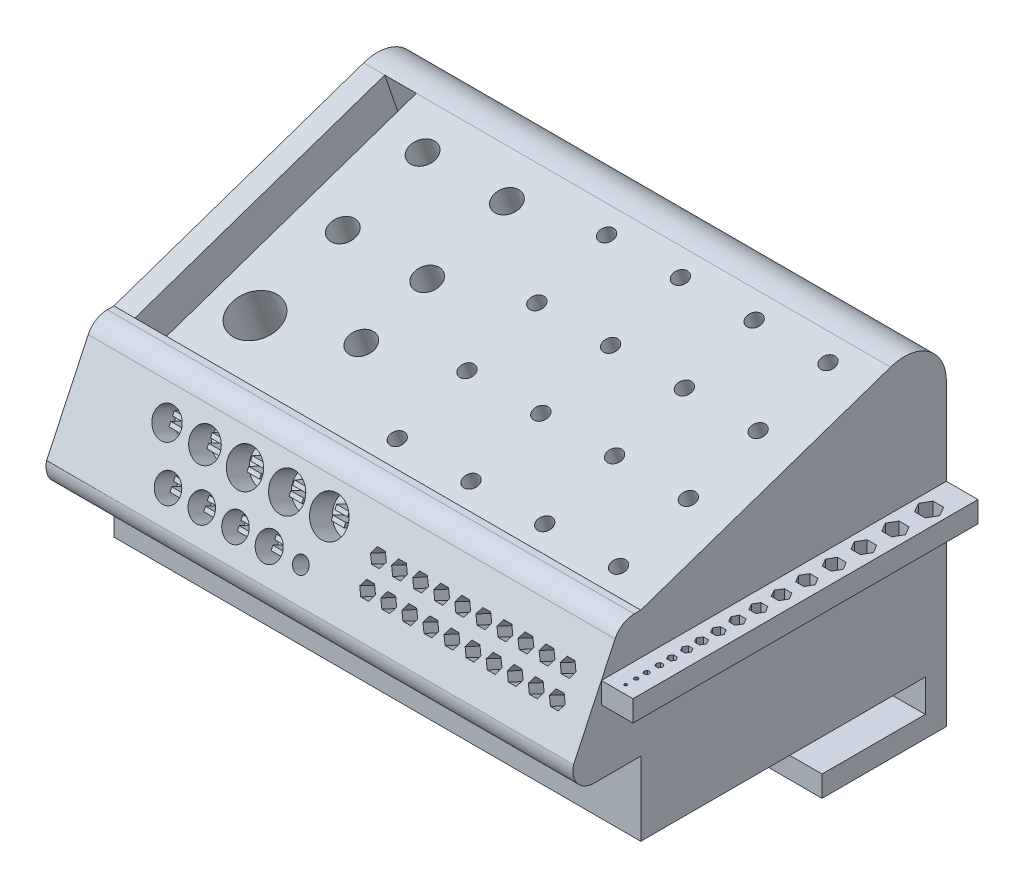
SolidWorks part; units mm, degrees
ref_plane "Front Plane" through (0, 0, 0) normal (0, 0, 1) x (1, 0, 0)
ref_plane "Top Plane" through (0, 0, 0) normal (0, 1, 0) x (1, 0, 0)
ref_plane "Right Plane" through (0, 0, 0) normal (1, 0, 0) x (0, 0, -1)
sketch "Sketch1" plane through (0, 0, 0) normal (1, 0, 0) x (0, 0, -1)
  line L0 (0, 0) -> (-49, 0)
  line L1 (0, 0) -> (0, 15.35)
  line L2 (-49, 0) -> (-49, -10)
  line L3 (-49, -10) -> (10, -10)
  line L4 (0, 15.35) -> (-135, 15.35)
  line L7 (-135, 15.35) -> (-135, 110.35)
  line L8 (10, -10) -> (10, 132.0117)
  line L9 (-135, 110.35) -> (-16.479, 150.9332)
  arc A0 (10, 132.0117) -> (-16.479, 150.9332) centre (-10, 132.0117) ccw
  point P11 (10, 160)
  dimension "D7" = 20
  dimension "D1" = 49
  dimension "D2" = 15.35
  dimension "D3" = 10
  dimension "D4" = 59
  dimension "D5" = 135
  dimension "D6" = 170
  dimension "D8" = 95
extrude "Boss-Extrude1" add sketch "Sketch1" along normal blind 250
sketch "Sketch2" plane through (0, 140.1443, 47.9874) normal (0, 0.9461, 0.3239) x (1, 0, 0)
  line L2 (250, -81.9723) -> (0, -81.9723) construction
  line L3 (250, 33.3043) -> (250, -91.9723) construction
  line L4 (0, 33.3043) -> (0, -91.9723) construction
  line L5 (0, -46.9723) -> (250, -46.9723) construction
  line L6 (0, -11.9723) -> (250, -11.9723) construction
  line L7 (250, 23.0277) -> (0, 23.0277) construction
  line L8 (230, -91.9723) -> (230, 33.3043) construction
  line L9 (250, -91.9723) -> (0, -91.9723) construction
  line L10 (250, 33.3043) -> (0, 33.3043) construction
  line L11 (195, -91.9723) -> (195, 33.3043) construction
  line L12 (160, -91.9723) -> (160, 33.3043) construction
  line L13 (125, -91.9723) -> (125, 33.3043) construction
  circle A0 centre (230, -81.9723) radius 3.5
  circle A1 centre (230, -46.9723) radius 3.5
  circle A2 centre (230, -11.9723) radius 3.5
  circle A3 centre (230, 23.0277) radius 3.5
  circle A5 centre (195, -81.9723) radius 3.5
  circle A6 centre (195, -46.9723) radius 3.5
  circle A7 centre (195, -11.9723) radius 3.5
  circle A8 centre (195, 23.0277) radius 3.5
  circle A9 centre (160, -81.9723) radius 3.5
  circle A10 centre (160, -46.9723) radius 3.5
  circle A11 centre (160, -11.9723) radius 3.5
  circle A12 centre (160, 23.0277) radius 3.5
  circle A13 centre (125, -81.9723) radius 3.5
  circle A14 centre (125, -46.9723) radius 3.5
  circle A15 centre (125, -11.9723) radius 3.5
  circle A16 centre (125, 23.0277) radius 3.5
  point P42 (230, -71.6708)
  point P45 (230, -1.6708)
  point P48 (230, 33.3292)
  point P49 (195, 33.3292)
  point P52 (195, -1.6708)
  point P55 (195, -36.6708)
  point P58 (195, -71.6708)
  point P61 (160, -71.6708)
  point P64 (125, -71.6708)
  point P65 (125, -36.6708)
  point P66 (125, -1.6708)
  point P67 (125, 33.3292)
  point P68 (125, 33.3292)
  point P69 (160, 33.3292)
  point P70 (160, -1.6708)
  point P71 (160, -36.6708)
  dimension "D1" = 10
  dimension "D2" = 35
  dimension "D3" = 35
  dimension "D4" = 35
  dimension "D5" = 20
  dimension "D6" = 35
  dimension "D7" = 35
  dimension "D8" = 35
extrude "Cut-Extrude1" cut sketch "Sketch2" against normal blind 80
sketch "Sketch3" plane through (0, 140.1443, 47.9874) normal (0, 0.9461, 0.3239) x (1, 0, 0)
  line L0 (105, 33.3043) -> (105, -91.9723) construction
  line L1 (250, 33.3043) -> (0, 33.3043) construction
  line L2 (250, -91.9723) -> (0, -91.9723) construction
  line L3 (105, 15.3043) -> (0, 15.3043) construction
  line L4 (0, 33.3043) -> (0, -91.9723) construction
  line L5 (85, 33.3043) -> (85, -91.9723) construction
  line L6 (105, -24.6957) -> (0, -24.6957) construction
  line L7 (105, -64.6957) -> (0, -64.6957) construction
  line L8 (45, 33.3043) -> (45, -91.9723) construction
  line L9 (25, 33.3043) -> (25, -91.9723) construction
  line L11 (25, 33.3043) -> (10, 33.3043)
  line L12 (25, 33.3043) -> (25, -91.9723)
  line L13 (25, -91.9723) -> (10, -91.9723)
  line L14 (10, 33.3043) -> (10, -91.9723)
  circle A0 centre (125, -46.9723) radius 3.5 construction
  circle A1 centre (85, 15.3043) radius 6
  circle A2 centre (85, -24.6957) radius 6
  circle A3 centre (85, -57.7346) radius 6
  circle A4 centre (45, 15.3043) radius 6
  circle A5 centre (45, -24.6957) radius 6
  circle A7 centre (45, -68.746) radius 11
  dimension "D2" = 12
  dimension "D11" = 22
  dimension "D1" = 20
  dimension "D3" = 18
  dimension "D4" = 20
  dimension "D5" = 40
  dimension "D6" = 40
  dimension "D7" = 40
  dimension "D8" = 20
  dimension "D9" = 15
  dimension "D10" = 0
extrude "Cut-Extrude3" cut sketch "Sketch3" against normal blind 80
sketch "Sketch5" plane through (0, 0, 135) normal (0, 0, 1) x (1, 0, 0)
  line L0 (250, 110.35) -> (250, 15.35) construction
  line L1 (250, 110.35) -> (0, 110.35)
  line L2 (250, 110.35) -> (250, 50.35)
  line L3 (250, 50.35) -> (0, 50.35)
  line L4 (0, 110.35) -> (0, 50.35)
  line L5 (0, 110.35) -> (0, 15.35) construction
  line L7 (250, 15.35) -> (0, 15.35) construction
  line L8 (250, 110.35) -> (25, 110.35) construction
  dimension "D1" = 35
  dimension "D2" = 0
extrude "Boss-Extrude3" add sketch "Sketch5" along normal blind 35
sketch "Sketch6" plane through (250, 0, 0) normal (1, 0, 0) x (0, 0, -1)
  line L0 (-135, 15.35) -> (-135, 110.35) construction
  line L1 (-135, 110.35) -> (-147.1922, 110.35) construction
  line L2 (-170, 110.35) -> (-135, 110.35) construction
  line L4 (-135, 50.35) -> (-157.1922, 50.35) construction
  line L5 (-157.1922, 50.35) -> (-170, 50.35)
  line L7 (-170, 110.35) -> (-170, 50.35)
  line L8 (-138.1305, 110.35) -> (-135, 110.35)
  line L9 (-166.8937, 62.7754) -> (-147.1763, 104.6131)
  arc A0 (-157.1922, 50.35) -> (-166.8937, 62.7754) centre (-157.1922, 60.35) cw
  arc A2 (-138.1305, 110.35) -> (-147.1763, 104.6131) centre (-138.1305, 100.35) ccw
  point P13 (-170, 50.35)
  point P15 (-170, 50.35)
  point P18 (-155, 110.35)
  dimension "D2" = 10
  dimension "D3" = 10
  dimension "D1" = 20
extrude "Cut-Extrude4" cut sketch "Sketch6" against normal through all
sketch "Sketch8" plane through (0, 75.7683, 160.7703) normal (0, 0.4263, 0.9046) x (1, 0, 0)
  line L0 (130, 29.3807) -> (130, -11.8503) construction
  line L1 (130, 8.7652) -> (250, 8.7652) construction
  line L2 (130, 2.7652) -> (250, 2.7652) construction
  line L3 (130, 14.7652) -> (250, 14.7652) construction
  line L4 (145, 14.7652) -> (145, 2.7652) construction
  line L5 (155, 14.7652) -> (155, 2.7652) construction
  line L6 (165, 14.7652) -> (165, 2.7652) construction
  line L7 (175, 14.7652) -> (175, 2.7652) construction
  line L8 (185, 14.7652) -> (185, 2.7652) construction
  line L9 (195, 14.7652) -> (195, 2.7652) construction
  line L10 (205, 14.7652) -> (205, 2.7652) construction
  line L11 (215, 14.7652) -> (215, 2.7652) construction
  line L12 (225, 14.7652) -> (225, 2.7652) construction
  line L13 (235, 14.7652) -> (235, 2.7652) construction
  line L14 (141.2472, 14.7652) -> (143.1236, 11.5152)
  line L15 (143.1236, 11.5152) -> (146.8764, 11.5152)
  line L16 (146.8764, 11.5152) -> (148.7528, 14.7652)
  line L17 (148.7528, 14.7652) -> (146.8764, 18.0152)
  line L18 (146.8764, 18.0152) -> (143.1236, 18.0152)
  line L19 (143.1236, 18.0152) -> (141.2472, 14.7652)
  line L20 (151.2472, 14.7652) -> (153.1236, 11.5152)
  line L21 (153.1236, 11.5152) -> (156.8764, 11.5152)
  line L22 (156.8764, 11.5152) -> (158.7528, 14.7652)
  line L23 (158.7528, 14.7652) -> (156.8764, 18.0152)
  line L24 (156.8764, 18.0152) -> (153.1236, 18.0152)
  line L25 (153.1236, 18.0152) -> (151.2472, 14.7652)
  line L26 (161.2472, 14.7652) -> (163.1236, 11.5152)
  line L27 (163.1236, 11.5152) -> (166.8764, 11.5152)
  line L28 (166.8764, 11.5152) -> (168.7528, 14.7652)
  line L29 (168.7528, 14.7652) -> (166.8764, 18.0152)
  line L30 (166.8764, 18.0152) -> (163.1236, 18.0152)
  line L31 (163.1236, 18.0152) -> (161.2472, 14.7652)
  line L32 (171.2472, 14.7652) -> (173.1236, 11.5152)
  line L33 (173.1236, 11.5152) -> (176.8764, 11.5152)
  line L34 (176.8764, 11.5152) -> (178.7528, 14.7652)
  line L35 (178.7528, 14.7652) -> (176.8764, 18.0152)
  line L36 (176.8764, 18.0152) -> (173.1236, 18.0152)
  line L37 (173.1236, 18.0152) -> (171.2472, 14.7652)
  line L38 (181.2472, 14.7652) -> (183.1236, 11.5152)
  line L39 (183.1236, 11.5152) -> (186.8764, 11.5152)
  line L40 (186.8764, 11.5152) -> (188.7528, 14.7652)
  line L41 (188.7528, 14.7652) -> (186.8764, 18.0152)
  line L42 (186.8764, 18.0152) -> (183.1236, 18.0152)
  line L43 (183.1236, 18.0152) -> (181.2472, 14.7652)
  line L44 (191.2472, 14.7652) -> (193.1236, 11.5152)
  line L45 (193.1236, 11.5152) -> (196.8764, 11.5152)
  line L46 (196.8764, 11.5152) -> (198.7528, 14.7652)
  line L47 (198.7528, 14.7652) -> (196.8764, 18.0152)
  line L48 (196.8764, 18.0152) -> (193.1236, 18.0152)
  line L49 (193.1236, 18.0152) -> (191.2472, 14.7652)
  line L50 (201.2472, 14.7652) -> (203.1236, 11.5152)
  line L51 (203.1236, 11.5152) -> (206.8764, 11.5152)
  line L52 (206.8764, 11.5152) -> (208.7528, 14.7652)
  line L53 (208.7528, 14.7652) -> (206.8764, 18.0152)
  line L54 (206.8764, 18.0152) -> (203.1236, 18.0152)
  line L55 (203.1236, 18.0152) -> (201.2472, 14.7652)
  line L56 (211.2472, 14.7652) -> (213.1236, 11.5152)
  line L57 (213.1236, 11.5152) -> (216.8764, 11.5152)
  line L58 (216.8764, 11.5152) -> (218.7528, 14.7652)
  line L59 (218.7528, 14.7652) -> (216.8764, 18.0152)
  line L60 (216.8764, 18.0152) -> (213.1236, 18.0152)
  line L61 (213.1236, 18.0152) -> (211.2472, 14.7652)
  line L62 (221.2472, 14.7652) -> (223.1236, 11.5152)
  line L63 (223.1236, 11.5152) -> (226.8764, 11.5152)
  line L64 (226.8764, 11.5152) -> (228.7528, 14.7652)
  line L65 (228.7528, 14.7652) -> (226.8764, 18.0152)
  line L66 (226.8764, 18.0152) -> (223.1236, 18.0152)
  line L67 (223.1236, 18.0152) -> (221.2472, 14.7652)
  line L68 (231.2472, 14.7652) -> (233.1236, 11.5152)
  line L69 (233.1236, 11.5152) -> (236.8764, 11.5152)
  line L70 (236.8764, 11.5152) -> (238.7528, 14.7652)
  line L71 (238.7528, 14.7652) -> (236.8764, 18.0152)
  line L72 (236.8764, 18.0152) -> (233.1236, 18.0152)
  line L73 (233.1236, 18.0152) -> (231.2472, 14.7652)
  line L74 (231.2472, 2.7652) -> (233.1236, -0.4848)
  line L75 (233.1236, -0.4848) -> (236.8764, -0.4848)
  line L76 (236.8764, -0.4848) -> (238.7528, 2.7652)
  line L77 (238.7528, 2.7652) -> (236.8764, 6.0152)
  line L78 (236.8764, 6.0152) -> (233.1236, 6.0152)
  line L79 (233.1236, 6.0152) -> (231.2472, 2.7652)
  line L80 (221.2472, 2.7652) -> (223.1236, -0.4848)
  line L81 (223.1236, -0.4848) -> (226.8764, -0.4848)
  line L82 (226.8764, -0.4848) -> (228.7528, 2.7652)
  line L83 (228.7528, 2.7652) -> (226.8764, 6.0152)
  line L84 (226.8764, 6.0152) -> (223.1236, 6.0152)
  line L85 (223.1236, 6.0152) -> (221.2472, 2.7652)
  line L86 (211.2472, 2.7652) -> (213.1236, -0.4848)
  line L87 (213.1236, -0.4848) -> (216.8764, -0.4848)
  line L88 (216.8764, -0.4848) -> (218.7528, 2.7652)
  line L89 (218.7528, 2.7652) -> (216.8764, 6.0152)
  line L90 (216.8764, 6.0152) -> (213.1236, 6.0152)
  line L91 (213.1236, 6.0152) -> (211.2472, 2.7652)
  line L92 (201.2472, 2.7652) -> (203.1236, -0.4848)
  line L93 (203.1236, -0.4848) -> (206.8764, -0.4848)
  line L94 (206.8764, -0.4848) -> (208.7528, 2.7652)
  line L95 (208.7528, 2.7652) -> (206.8764, 6.0152)
  line L96 (206.8764, 6.0152) -> (203.1236, 6.0152)
  line L97 (203.1236, 6.0152) -> (201.2472, 2.7652)
  line L98 (191.2472, 2.7652) -> (193.1236, -0.4848)
  line L99 (193.1236, -0.4848) -> (196.8764, -0.4848)
  line L100 (196.8764, -0.4848) -> (198.7528, 2.7652)
  line L101 (198.7528, 2.7652) -> (196.8764, 6.0152)
  line L102 (196.8764, 6.0152) -> (193.1236, 6.0152)
  line L103 (193.1236, 6.0152) -> (191.2472, 2.7652)
  line L104 (181.2472, 2.7652) -> (183.1236, -0.4848)
  line L105 (183.1236, -0.4848) -> (186.8764, -0.4848)
  line L106 (186.8764, -0.4848) -> (188.7528, 2.7652)
  line L107 (188.7528, 2.7652) -> (186.8764, 6.0152)
  line L108 (186.8764, 6.0152) -> (183.1236, 6.0152)
  line L109 (183.1236, 6.0152) -> (181.2472, 2.7652)
  line L110 (171.2472, 2.7652) -> (173.1236, -0.4848)
  line L111 (173.1236, -0.4848) -> (176.8764, -0.4848)
  line L112 (176.8764, -0.4848) -> (178.7528, 2.7652)
  line L113 (178.7528, 2.7652) -> (176.8764, 6.0152)
  line L114 (176.8764, 6.0152) -> (173.1236, 6.0152)
  line L115 (173.1236, 6.0152) -> (171.2472, 2.7652)
  line L116 (161.2472, 2.7652) -> (163.1236, -0.4848)
  line L117 (163.1236, -0.4848) -> (166.8764, -0.4848)
  line L118 (166.8764, -0.4848) -> (168.7528, 2.7652)
  line L119 (168.7528, 2.7652) -> (166.8764, 6.0152)
  line L120 (166.8764, 6.0152) -> (163.1236, 6.0152)
  line L121 (163.1236, 6.0152) -> (161.2472, 2.7652)
  line L122 (151.2472, 2.7652) -> (153.1236, -0.4848)
  line L123 (153.1236, -0.4848) -> (156.8764, -0.4848)
  line L124 (156.8764, -0.4848) -> (158.7528, 2.7652)
  line L125 (158.7528, 2.7652) -> (156.8764, 6.0152)
  line L126 (156.8764, 6.0152) -> (153.1236, 6.0152)
  line L127 (153.1236, 6.0152) -> (151.2472, 2.7652)
  line L128 (141.2472, 2.7652) -> (143.1236, -0.4848)
  line L129 (143.1236, -0.4848) -> (146.8764, -0.4848)
  line L130 (146.8764, -0.4848) -> (148.7528, 2.7652)
  line L131 (148.7528, 2.7652) -> (146.8764, 6.0152)
  line L132 (146.8764, 6.0152) -> (143.1236, 6.0152)
  line L133 (143.1236, 6.0152) -> (141.2472, 2.7652)
  line L134 (250, -14.3635) -> (250, 31.8877) construction
  line L135 (250, 31.8877) -> (0, 31.8877) construction
  circle A0 centre (145, 14.7652) radius 3.25 construction
  circle A1 centre (155, 14.7652) radius 3.25 construction
  circle A2 centre (165, 14.7652) radius 3.25 construction
  circle A3 centre (175, 14.7652) radius 3.25 construction
  circle A4 centre (185, 14.7652) radius 3.25 construction
  circle A5 centre (195, 14.7652) radius 3.25 construction
  circle A6 centre (205, 14.7652) radius 3.25 construction
  circle A7 centre (215, 14.7652) radius 3.25 construction
  circle A8 centre (225, 14.7652) radius 3.25 construction
  circle A9 centre (235, 14.7652) radius 3.25 construction
  circle A10 centre (235, 2.7652) radius 3.25 construction
  circle A11 centre (225, 2.7652) radius 3.25 construction
  circle A12 centre (215, 2.7652) radius 3.25 construction
  circle A13 centre (205, 2.7652) radius 3.25 construction
  circle A14 centre (195, 2.7652) radius 3.25 construction
  circle A15 centre (185, 2.7652) radius 3.25 construction
  circle A16 centre (175, 2.7652) radius 3.25 construction
  circle A17 centre (165, 2.7652) radius 3.25 construction
  circle A18 centre (155, 2.7652) radius 3.25 construction
  circle A19 centre (145, 2.7652) radius 3.25 construction
  dimension "D12" = 6.5
  dimension "D13" = 6.5
  dimension "D14" = 6.5
  dimension "D15" = 6.5
  dimension "D16" = 6.5
  dimension "D17" = 6.5
  dimension "D18" = 6.5
  dimension "D19" = 6.5
  dimension "D20" = 6.5
  dimension "D21" = 6.5
  dimension "D22" = 6.5
  dimension "D23" = 6.5
  dimension "D24" = 6.5
  dimension "D25" = 6.5
  dimension "D26" = 6.5
  dimension "D27" = 6.5
  dimension "D28" = 6.5
  dimension "D29" = 6.5
  dimension "D30" = 6.5
  dimension "D31" = 6.5
  dimension "D1" = 6
  dimension "D2" = 6
  dimension "D3" = 10
  dimension "D4" = 10
  dimension "D5" = 10
  dimension "D6" = 10
  dimension "D7" = 10
  dimension "D8" = 10
  dimension "D9" = 10
  dimension "D10" = 10
  dimension "D11" = 10
  dimension "D32" = 15
  dimension "D33" = 23.1225
extrude "Cut-Extrude6" cut sketch "Sketch8" against normal blind 15
sketch "Sketch9" plane through (0, 75.7683, 160.7703) normal (0, 0.4263, 0.9046) x (1, 0, 0)
  line L0 (130, 31.8877) -> (130, -14.3635) construction
  line L1 (250, 31.8877) -> (0, 31.8877) construction
  line L2 (250, -14.3635) -> (0, -14.3635) construction
  line L3 (250, -14.3635) -> (250, 31.8877) construction
  line L4 (130, 8.7621) -> (0, 8.7621) construction
  line L5 (0, 31.8877) -> (0, -14.3635) construction
  line L6 (130, 18.7621) -> (0, 18.7621) construction
  line L7 (130, -1.2379) -> (0, -1.2379) construction
  circle A0 centre (120, 18.7621) radius 8.625
  circle A1 centre (100, 18.7621) radius 8.125
  circle A2 centre (80, 18.7621) radius 8.125
  circle A3 centre (61, 18.7621) radius 7.125
  circle A4 centre (43, 18.7621) radius 6.625
  circle A5 centre (100, -1.2379) radius 6.125
  circle A6 centre (115, -1.2379) radius 3.625
  circle A7 centre (84, -1.2379) radius 6
  circle A8 centre (68, -1.2379) radius 6
  circle A9 centre (52, -1.2379) radius 6
  dimension "D4" = 17.25
  dimension "D6" = 16.25
  dimension "D8" = 16.25
  dimension "D10" = 14.25
  dimension "D12" = 13.25
  dimension "D14" = 12.25
  dimension "D15" = 7.25
  dimension "D18" = 12
  dimension "D20" = 12
  dimension "D22" = 12
  dimension "D1" = 120
  dimension "D2" = 10
  dimension "D3" = 10
  dimension "D5" = 10
  dimension "D7" = 20
  dimension "D9" = 20
  dimension "D11" = 19
  dimension "D13" = 18
  dimension "D16" = 15
  dimension "D17" = 15
  dimension "D19" = 16
  dimension "D21" = 16
  dimension "D23" = 16
extrude "Cut-Extrude7" cut sketch "Sketch9" against normal blind 12
sketch "Sketch10" plane through (0, 70.6525, 149.9154) normal (0, 0.4263, 0.9046) x (1, 0, 0)
  line L0 (120, 27.3871) -> (120, 10.1371) construction
  line L1 (128.625, 18.7621) -> (111.375, 18.7621) construction
  line L2 (111.375, 18.7621) -> (108.125, 18.7621) construction
  line L3 (108.125, 18.7621) -> (91.875, 18.7621) construction
  line L4 (91.875, 18.7621) -> (88.125, 18.7621) construction
  line L5 (88.125, 18.7621) -> (71.875, 18.7621) construction
  line L6 (71.875, 18.7621) -> (68.125, 18.7621) construction
  line L7 (68.125, 18.7621) -> (53.875, 18.7621) construction
  line L8 (53.875, 18.7621) -> (49.625, 18.7621) construction
  line L9 (49.625, 18.7621) -> (36.375, 18.7621) construction
  line L10 (46, -1.2379) -> (58, -1.2379) construction
  line L11 (58, -1.2379) -> (62, -1.2379) construction
  line L12 (62, -1.2379) -> (74, -1.2379) construction
  line L13 (74, -1.2379) -> (78, -1.2379) construction
  line L14 (78, -1.2379) -> (90, -1.2379) construction
  line L15 (90, -1.2379) -> (93.875, -1.2379) construction
  line L16 (93.875, -1.2379) -> (106.125, -1.2379) construction
  line L17 (106.125, -1.2379) -> (111.375, -1.2379) construction
  line L18 (111.375, -1.2379) -> (118.625, -1.2379) construction
  line L19 (100, 26.8871) -> (100, 10.6371) construction
  line L20 (80, 26.8871) -> (80, 10.6371) construction
  line L21 (61, 25.8871) -> (61, 11.6371) construction
  line L22 (43, 25.3871) -> (43, 12.1371) construction
  line L23 (52, 4.7621) -> (52, -7.2379) construction
  line L24 (68, 4.7621) -> (68, -7.2379) construction
  line L25 (84, 4.7621) -> (84, -7.2379) construction
  line L26 (100, 4.8871) -> (100, -7.3629) construction
  line L27 (115, 2.3871) -> (115, -4.8629) construction
  line L28 (97, 21.7621) -> (103, 21.7621)
  line L33 (117, 21.7621) -> (123, 21.7621)
  line L34 (117, 21.7621) -> (117, 19.7621)
  line L39 (117, 19.7621) -> (123, 19.7621)
  line L40 (123, 21.7621) -> (123, 19.7621)
  line L41 (117, 17.7621) -> (123, 17.7621)
  line L42 (117, 17.7621) -> (117, 15.7621)
  line L43 (117, 15.7621) -> (123, 15.7621)
  line L44 (123, 17.7621) -> (123, 15.7621)
  line L45 (97, 21.7621) -> (97, 19.7621)
  line L46 (97, 19.7621) -> (103, 19.7621)
  line L47 (103, 21.7621) -> (103, 19.7621)
  line L48 (97, 17.7621) -> (103, 17.7621)
  line L49 (97, 17.7621) -> (97, 15.7621)
  line L50 (97, 15.7621) -> (103, 15.7621)
  line L51 (103, 17.7621) -> (103, 15.7621)
  line L52 (77, 21.7621) -> (83, 21.7621)
  line L53 (77, 21.7621) -> (77, 19.7621)
  line L54 (77, 19.7621) -> (83, 19.7621)
  line L55 (83, 21.7621) -> (83, 19.7621)
  line L56 (77, 17.7621) -> (83, 17.7621)
  line L57 (77, 17.7621) -> (77, 15.7621)
  line L58 (77, 15.7621) -> (83, 15.7621)
  line L59 (83, 17.7621) -> (83, 15.7621)
  line L60 (58.0009, 21.7621) -> (64.0009, 21.7621)
  line L61 (58.0009, 21.7621) -> (58.0009, 19.7621)
  line L62 (58.0009, 19.7621) -> (64.0009, 19.7621)
  line L63 (64.0009, 21.7621) -> (64.0009, 19.7621)
  line L64 (58, 17.7621) -> (64, 17.7621)
  line L65 (58, 17.7621) -> (58, 15.7621)
  line L66 (58, 15.7621) -> (64, 15.7621)
  line L67 (64, 17.7621) -> (64, 15.7621)
  line L68 (40, 21.7621) -> (46, 21.7621)
  line L69 (40, 21.7621) -> (40, 19.7621)
  line L70 (40, 19.7621) -> (46, 19.7621)
  line L71 (46, 21.7621) -> (46, 19.7621)
  line L72 (40, 17.7621) -> (46, 17.7621)
  line L73 (40, 17.7621) -> (40, 15.7621)
  line L74 (40, 15.7621) -> (46, 15.7621)
  line L75 (46, 17.7621) -> (46, 15.7621)
  line L76 (49, 1.7621) -> (55, 1.7621)
  line L77 (49, 1.7621) -> (49, -0.2379)
  line L78 (49, -0.2379) -> (55, -0.2379)
  line L79 (55, 1.7621) -> (55, -0.2379)
  line L80 (49, -2.2379) -> (55, -2.2379)
  line L81 (49, -2.2379) -> (49, -4.2379)
  line L82 (49, -4.2379) -> (55, -4.2379)
  line L83 (55, -2.2379) -> (55, -4.2379)
  line L84 (65, 1.7621) -> (71, 1.7621)
  line L85 (65, 1.7621) -> (65, -0.2379)
  line L86 (65, -0.2379) -> (71, -0.2379)
  line L87 (71, 1.7621) -> (71, -0.2379)
  line L88 (65, -2.2379) -> (71, -2.2379)
  line L89 (65, -2.2379) -> (65, -4.2379)
  line L90 (65, -4.2379) -> (71, -4.2379)
  line L91 (71, -2.2379) -> (71, -4.2379)
  line L92 (81, 1.7621) -> (87, 1.7621)
  line L93 (81, 1.7621) -> (81, -0.2379)
  line L94 (81, -0.2379) -> (87, -0.2379)
  line L95 (87, 1.7621) -> (87, -0.2379)
  line L96 (81, -2.2379) -> (87, -2.2379)
  line L97 (81, -2.2379) -> (81, -4.2379)
  line L98 (81, -4.2379) -> (87, -4.2379)
  line L99 (87, -2.2379) -> (87, -4.2379)
  line L100 (97, 1.7621) -> (103, 1.7621)
  line L101 (97, 1.7621) -> (97, -0.2379)
  line L102 (97, -0.2379) -> (103, -0.2379)
  line L103 (103, 1.7621) -> (103, -0.2379)
  line L104 (97, -2.2379) -> (103, -2.2379)
  line L105 (97, -2.2379) -> (97, -4.2379)
  line L106 (97, -4.2379) -> (103, -4.2379)
  line L107 (103, -2.2379) -> (103, -4.2379)
  circle A0 centre (120, 18.7621) radius 8.625 construction
  circle A1 centre (120, 18.7621) radius 8.625 construction
  circle A2 centre (100, 18.7621) radius 8.125 construction
  circle A3 centre (100, 18.7621) radius 8.125 construction
  circle A4 centre (80, 18.7621) radius 8.125 construction
  circle A5 centre (61, 18.7621) radius 7.125 construction
  circle A6 centre (43, 18.7621) radius 6.625 construction
  circle A7 centre (43, 18.7621) radius 6.625 construction
  circle A8 centre (52, -1.2379) radius 6 construction
  circle A9 centre (52, -1.2379) radius 6 construction
  circle A10 centre (68, -1.2379) radius 6 construction
  circle A11 centre (68, -1.2379) radius 6 construction
  circle A12 centre (84, -1.2379) radius 6 construction
  circle A13 centre (84, -1.2379) radius 6 construction
  circle A14 centre (100, -1.2379) radius 6.125 construction
  circle A15 centre (115, -1.2379) radius 3.625 construction
  circle A16 centre (115, -1.2379) radius 3.625 construction
  circle A17 centre (80, 18.7621) radius 8.125 construction
  circle A18 centre (61, 18.7621) radius 7.125 construction
  circle A19 centre (100, -1.2379) radius 6.125 construction
  point P90 (120, 18.7621)
  point P95 (120, 18.7621)
  point P148 (100, 18.7621)
  point P165 (80, 18.7621)
  point P166 (46, 16.7621)
  dimension "D1" = 2
  dimension "D2" = 2
  dimension "D3" = 3
  dimension "D4" = 6
  dimension "D5" = 6
  dimension "D6" = 3
  dimension "D7" = 3
  dimension "D8" = 3
  dimension "D9" = 6
  dimension "D10" = 6
  dimension "D11" = 6
  dimension "D12" = 6
  dimension "D13" = 2
  dimension "D14" = 2
  dimension "D15" = 3
  dimension "D16" = 3
  dimension "D17" = 3
  dimension "D18" = 3
  dimension "D19" = 6
  dimension "D20" = 6
  dimension "D21" = 2
  dimension "D22" = 2
  dimension "D23" = 2
  dimension "D24" = 2
  dimension "D25" = 2
  dimension "D26" = 2
  dimension "D27" = 6
  dimension "D28" = 6
  dimension "D29" = 3
  dimension "D30" = 3
  dimension "D31" = 3
  dimension "D32" = 3
  dimension "D33" = 3.0009
  dimension "D34" = 3
  dimension "D35" = 3
  dimension "D36" = 3
  dimension "D37" = 3
  dimension "D38" = 3
  dimension "D39" = 3
  dimension "D40" = 3
  dimension "D41" = 2
  dimension "D42" = 2
  dimension "D43" = 2
  dimension "D44" = 2
  dimension "D45" = 2
  dimension "D46" = 2
  dimension "D47" = 2
  dimension "D48" = 2
  dimension "D49" = 6
  dimension "D50" = 6
  dimension "D51" = 6
  dimension "D52" = 6
  dimension "D53" = 6
  dimension "D54" = 6
  dimension "D55" = 6
  dimension "D56" = 6
  dimension "D57" = 3
  dimension "D58" = 3
  dimension "D59" = 3
  dimension "D60" = 3
  dimension "D61" = 3
  dimension "D62" = 3
  dimension "D63" = 3
  dimension "D64" = 3
  dimension "D65" = 3
  dimension "D66" = 3
  dimension "D67" = 3
  dimension "D68" = 3
  dimension "D69" = 3
  dimension "D70" = 3
  dimension "D71" = 3
  dimension "D72" = 3
extrude "Boss-Extrude4" add sketch "Sketch10" along normal blind 6.25
sketch "Sketch11" plane through (250, 0, 0) normal (1, 0, 0) x (0, 0, -1)
  line L0 (10, -10) -> (10, 132.0117) construction
  line L1 (-166.8937, 62.7754) -> (-147.1763, 104.6131) construction
  line L2 (10, 80.7911) -> (-153.6903, 80.7911)
  line L3 (10, 80.7911) -> (10, 90.7911)
  line L4 (10, 90.7911) -> (-153.6903, 90.7911)
  line L5 (-153.6903, 80.7911) -> (-153.6903, 90.7911)
  dimension "D1" = 10
extrude "Boss-Extrude5" add sketch "Sketch11" along normal blind 15
sketch "Sketch12" plane through (0, 90.7911, 0) normal (0, 1, 0) x (1, 0, 0)
  line L0 (250, 10) -> (265, 10) construction
  line L1 (265, 10) -> (265, -153.6903) construction
  line L2 (265, -153.6903) -> (250, -153.6903) construction
  line L3 (250, -153.6903) -> (250, 10) construction
  line L4 (257.5, 10) -> (257.5, -153.6903) construction
  line L6 (258.2217, -149.6903) -> (257.8608, -149.0653)
  line L7 (257.8608, -149.0653) -> (257.1392, -149.0653)
  line L8 (257.1392, -149.0653) -> (256.7783, -149.6903)
  line L9 (256.7783, -149.6903) -> (257.1392, -150.3153)
  line L10 (257.1392, -150.3153) -> (257.8608, -150.3153)
  line L11 (257.8608, -150.3153) -> (258.2217, -149.6903)
  line L12 (258.5104, -144.6903) -> (258.0052, -143.8153)
  line L13 (258.0052, -143.8153) -> (256.9948, -143.8153)
  line L14 (256.9948, -143.8153) -> (256.4896, -144.6903)
  line L15 (256.4896, -144.6903) -> (256.9948, -145.5653)
  line L16 (256.9948, -145.5653) -> (258.0052, -145.5653)
  line L17 (258.0052, -145.5653) -> (258.5104, -144.6903)
  line L18 (258.799, -139.6903) -> (258.1495, -138.5653)
  line L19 (258.1495, -138.5653) -> (256.8505, -138.5653)
  line L20 (256.8505, -138.5653) -> (256.201, -139.6903)
  line L21 (256.201, -139.6903) -> (256.8505, -140.8153)
  line L22 (256.8505, -140.8153) -> (258.1495, -140.8153)
  line L23 (258.1495, -140.8153) -> (258.799, -139.6903)
  line L24 (259.0877, -133.6903) -> (258.2939, -132.3153)
  line L25 (258.2939, -132.3153) -> (256.7061, -132.3153)
  line L26 (256.7061, -132.3153) -> (255.9123, -133.6903)
  line L27 (255.9123, -133.6903) -> (256.7061, -135.0653)
  line L28 (256.7061, -135.0653) -> (258.2939, -135.0653)
  line L29 (258.2939, -135.0653) -> (259.0877, -133.6903)
  line L30 (259.3764, -127.6903) -> (258.4382, -126.0653)
  line L31 (258.4382, -126.0653) -> (256.5618, -126.0653)
  line L32 (256.5618, -126.0653) -> (255.6236, -127.6903)
  line L33 (255.6236, -127.6903) -> (256.5618, -129.3153)
  line L34 (256.5618, -129.3153) -> (258.4382, -129.3153)
  line L35 (258.4382, -129.3153) -> (259.3764, -127.6903)
  line L36 (259.6651, -120.6903) -> (258.5825, -118.8153)
  line L37 (258.5825, -118.8153) -> (256.4175, -118.8153)
  line L38 (256.4175, -118.8153) -> (255.3349, -120.6903)
  line L39 (255.3349, -120.6903) -> (256.4175, -122.5653)
  line L40 (256.4175, -122.5653) -> (258.5825, -122.5653)
  line L41 (258.5825, -122.5653) -> (259.6651, -120.6903)
  line L42 (259.9537, -113.6903) -> (258.7269, -111.5653)
  line L43 (258.7269, -111.5653) -> (256.2731, -111.5653)
  line L44 (256.2731, -111.5653) -> (255.0463, -113.6903)
  line L45 (255.0463, -113.6903) -> (256.2731, -115.8153)
  line L46 (256.2731, -115.8153) -> (258.7269, -115.8153)
  line L47 (258.7269, -115.8153) -> (259.9537, -113.6903)
  line L48 (260.2424, -105.6903) -> (258.8712, -103.3153)
  line L49 (258.8712, -103.3153) -> (256.1288, -103.3153)
  line L50 (256.1288, -103.3153) -> (254.7576, -105.6903)
  line L51 (254.7576, -105.6903) -> (256.1288, -108.0653)
  line L52 (256.1288, -108.0653) -> (258.8712, -108.0653)
  line L53 (258.8712, -108.0653) -> (260.2424, -105.6903)
  line L54 (260.5311, -96.6903) -> (259.0155, -94.0653)
  line L55 (259.0155, -94.0653) -> (255.9845, -94.0653)
  line L56 (255.9845, -94.0653) -> (254.4689, -96.6903)
  line L57 (254.4689, -96.6903) -> (255.9845, -99.3153)
  line L58 (255.9845, -99.3153) -> (259.0155, -99.3153)
  line L59 (259.0155, -99.3153) -> (260.5311, -96.6903)
  line L60 (260.8198, -86.6903) -> (259.1599, -83.8153)
  line L61 (259.1599, -83.8153) -> (255.8401, -83.8153)
  line L62 (255.8401, -83.8153) -> (254.1802, -86.6903)
  line L63 (254.1802, -86.6903) -> (255.8401, -89.5653)
  line L64 (255.8401, -89.5653) -> (259.1599, -89.5653)
  line L65 (259.1599, -89.5653) -> (260.8198, -86.6903)
  line L66 (261.1084, -75.6903) -> (259.3042, -72.5653)
  line L67 (259.3042, -72.5653) -> (255.6958, -72.5653)
  line L68 (255.6958, -72.5653) -> (253.8916, -75.6903)
  line L69 (253.8916, -75.6903) -> (255.6958, -78.8153)
  line L70 (255.6958, -78.8153) -> (259.3042, -78.8153)
  line L71 (259.3042, -78.8153) -> (261.1084, -75.6903)
  line L72 (261.3971, -63.6903) -> (259.4486, -60.3153)
  line L73 (259.4486, -60.3153) -> (255.5514, -60.3153)
  line L74 (255.5514, -60.3153) -> (253.6029, -63.6903)
  line L75 (253.6029, -63.6903) -> (255.5514, -67.0653)
  line L76 (255.5514, -67.0653) -> (259.4486, -67.0653)
  line L77 (259.4486, -67.0653) -> (261.3971, -63.6903)
  line L78 (261.6858, -50.6903) -> (259.5929, -47.0653)
  line L79 (259.5929, -47.0653) -> (255.4071, -47.0653)
  line L80 (255.4071, -47.0653) -> (253.3142, -50.6903)
  line L81 (253.3142, -50.6903) -> (255.4071, -54.3153)
  line L82 (255.4071, -54.3153) -> (259.5929, -54.3153)
  line L83 (259.5929, -54.3153) -> (261.6858, -50.6903)
  line L84 (261.9745, -36.6903) -> (259.7372, -32.8153)
  line L85 (259.7372, -32.8153) -> (255.2628, -32.8153)
  line L86 (255.2628, -32.8153) -> (253.0255, -36.6903)
  line L87 (253.0255, -36.6903) -> (255.2628, -40.5653)
  line L88 (255.2628, -40.5653) -> (259.7372, -40.5653)
  line L89 (259.7372, -40.5653) -> (261.9745, -36.6903)
  line L90 (252.7369, -21.6903) -> (255.1184, -25.8153)
  line L91 (255.1184, -25.8153) -> (259.8816, -25.8153)
  line L92 (259.8816, -25.8153) -> (262.2631, -21.6903)
  line L93 (262.2631, -21.6903) -> (259.8816, -17.5653)
  line L94 (259.8816, -17.5653) -> (255.1184, -17.5653)
  line L95 (255.1184, -17.5653) -> (252.7369, -21.6903)
  line L96 (252.4482, -5.6903) -> (254.9741, -10.0653)
  line L97 (254.9741, -10.0653) -> (260.0259, -10.0653)
  line L98 (260.0259, -10.0653) -> (262.5518, -5.6903)
  line L99 (262.5518, -5.6903) -> (260.0259, -1.3153)
  line L100 (260.0259, -1.3153) -> (254.9741, -1.3153)
  line L101 (254.9741, -1.3153) -> (252.4482, -5.6903)
  circle A0 centre (257.5, -149.6903) radius 0.625 construction
  circle A1 centre (257.5, -144.6903) radius 0.875 construction
  circle A2 centre (257.5, -139.6903) radius 1.125 construction
  circle A3 centre (257.5, -133.6903) radius 1.375 construction
  circle A4 centre (257.5, -127.6903) radius 1.625 construction
  circle A5 centre (257.5, -120.6903) radius 1.875 construction
  circle A6 centre (257.5, -113.6903) radius 2.125 construction
  circle A7 centre (257.5, -105.6903) radius 2.375 construction
  circle A8 centre (257.5, -96.6903) radius 2.625 construction
  circle A9 centre (257.5, -86.6903) radius 2.875 construction
  circle A10 centre (257.5, -75.6903) radius 3.125 construction
  circle A11 centre (257.5, -63.6903) radius 3.375 construction
  circle A12 centre (257.5, -50.6903) radius 3.625 construction
  circle A13 centre (257.5, -36.6903) radius 3.875 construction
  circle A14 centre (257.5, -21.6903) radius 4.125 construction
  circle A15 centre (257.5, -5.6903) radius 4.375 construction
  dimension "D1" = 1.25
  dimension "D2" = 1.75
  dimension "D5" = 2.25
  dimension "D7" = 2.75
  dimension "D9" = 3.25
  dimension "D11" = 3.75
  dimension "D13" = 4.25
  dimension "D15" = 4.75
  dimension "D17" = 5.25
  dimension "D20" = 5.75
  dimension "D21" = 6.25
  dimension "D23" = 6.75
  dimension "D26" = 7.25
  dimension "D27" = 7.75
  dimension "D30" = 8.25
  dimension "D32" = 8.75
  dimension "D3" = 4
  dimension "D4" = 5
  dimension "D6" = 5
  dimension "D8" = 6
  dimension "D10" = 6
  dimension "D12" = 7
  dimension "D14" = 7
  dimension "D16" = 8
  dimension "D18" = 9
  dimension "D19" = 10
  dimension "D22" = 11
  dimension "D24" = 12
  dimension "D25" = 13
  dimension "D28" = 14
  dimension "D29" = 15
  dimension "D31" = 16
extrude "Cut-Extrude8" cut sketch "Sketch12" against normal through all
